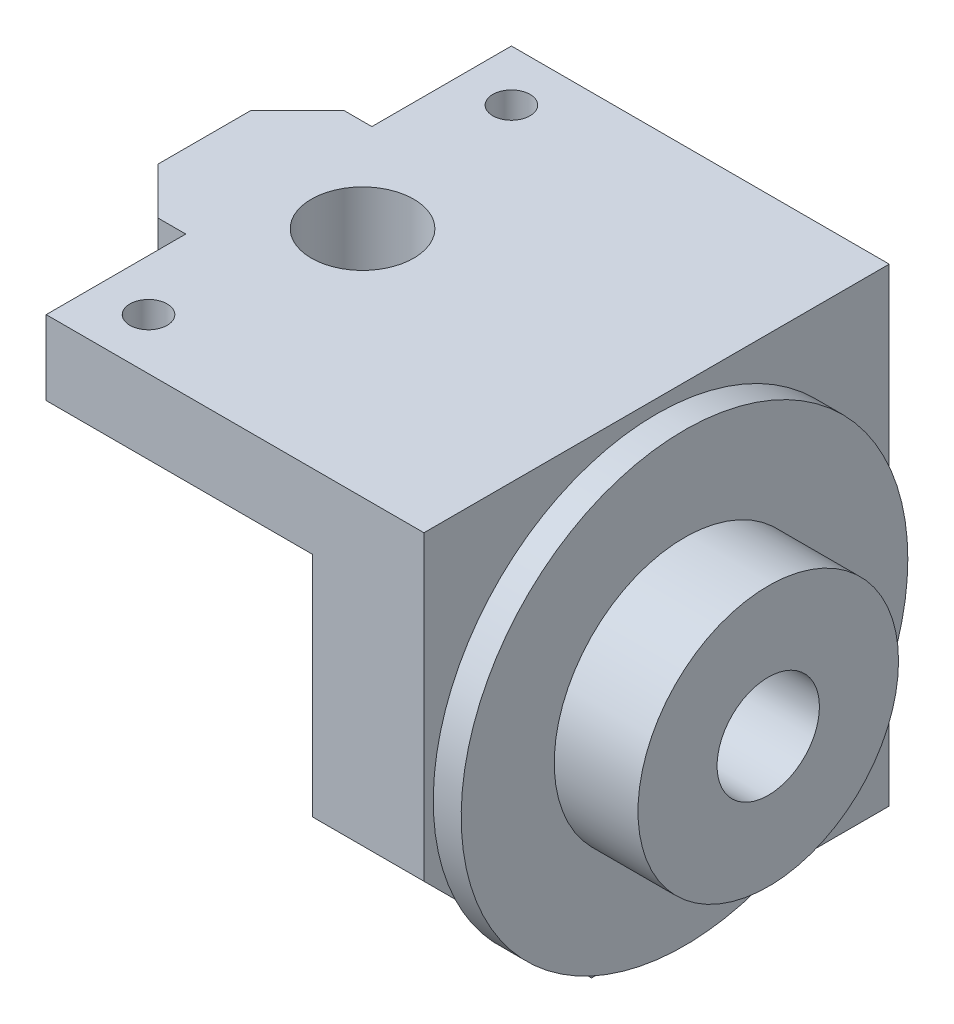
SolidWorks part; units mm, degrees
material "3.0205 (EN-AW 1200)"
ref_plane "Plan de face" through (0, 0, 0) normal (0, 0, 1) x (1, 0, 0)
ref_plane "Plan de dessus" through (0, 0, 0) normal (0, 1, 0) x (1, 0, 0)
ref_plane "Plan de droite" through (0, 0, 0) normal (1, 0, 0) x (0, 0, -1)
sketch "Esquisse1" plane through (0, 0, 0) normal (0, 1, 0) x (1, 0, 0)
  line L1 (-46.9861, 29.5221) -> (-6.3861, 29.5221)
  line L2 (-46.9861, 29.5221) -> (-46.9861, -20.4779)
  line L3 (-46.9861, -20.4779) -> (-6.3861, -20.4779)
  line L4 (-6.3861, 29.5221) -> (-6.3861, -20.4779)
  dimension "D1" = 50
  dimension "D2" = 40.6
extrude "Boss.-Extru.1" add sketch "Esquisse1" along normal blind 8
sketch "Esquisse2" plane through (0, 0, 0) normal (0, -1, 0) x (-1, 0, 0)
  line L0 (6.3861, 29.5221) -> (46.9861, 29.5221) construction
  line L1 (6.3861, -20.4779) -> (18.3861, -20.4779)
  line L2 (6.3861, -20.4779) -> (6.3861, 29.5221)
  line L3 (6.3861, 29.5221) -> (18.3861, 29.5221)
  line L4 (18.3861, -20.4779) -> (18.3861, 29.5221)
  dimension "D1" = 12
extrude "Boss.-Extru.2" add sketch "Esquisse2" along normal blind 42.44
chamfer "Chanfrein1" distance 18 distance2 18 1 edges at (-12.3861, -42.44, 20.4779)
sketch "Esquisse3" plane through (-6.3861, 0, 0) normal (1, 0, 0) x (0, 0, -1)
  line L0 (29.5221, 8) -> (29.5221, -42.44) construction
  line L1 (29.5221, -42.44) -> (-2.4779, -42.44) construction
  circle A0 centre (4.5221, -17.44) radius 24
  dimension "D1" = 48
  dimension "D2" = 25
  dimension "D3" = 25
extrude "Boss.-Extru.3" add sketch "Esquisse3" along normal blind 3
sketch "Esquisse4" plane through (-3.3861, 0, 0) normal (1, 0, 0) x (0, 0, -1)
  circle A0 centre (4.5221, -17.44) radius 14
  circle A1 centre (4.5221, -17.44) radius 24 construction
  dimension "D1" = 28
  dimension "D2" = 0
extrude "Boss.-Extru.4" add sketch "Esquisse4" along normal blind 9
sketch "Esquisse5" plane through (-46.9861, 0, 0) normal (-1, 0, 0) x (0, 0, 1)
  line L0 (-29.5221, 8) -> (20.4779, 8) construction
  line L1 (-14.5221, 8) -> (5.4779, 8)
  line L2 (-14.5221, 8) -> (-14.5221, 0)
  line L3 (-14.5221, 0) -> (5.4779, 0)
  line L4 (5.4779, 8) -> (5.4779, 0)
  line L5 (-29.5221, 0) -> (20.4779, 0) construction
  dimension "D1" = 15
  dimension "D2" = 15
  dimension "D3" = 20
extrude "Boss.-Extru.5" add sketch "Esquisse5" along normal blind 8
chamfer "Chanfrein2" distance 5 angle 45 1 edges at (-54.9861, 4, 5.4779)
chamfer "Chanfrein3" distance 5 angle 45 1 edges at (-54.9861, 4, -14.5221)
sketch "Esquisse6" plane through (0, 8, 0) normal (0, 1, 0) x (1, 0, 0)
  line L1 (-6.3861, 29.5221) -> (-46.9861, 29.5221) construction
  line L2 (-54.9861, -0.4779) -> (-54.9861, 9.5221) construction
  circle A0 centre (-37.9861, 4.5221) radius 5.5
  dimension "D1" = 11
  dimension "D2" = 25
  dimension "D3" = 17
extrude "Enlèv. mat.-Extru.1" cut sketch "Esquisse6" against normal through all
sketch "Esquisse7" plane through (5.6139, 0, 0) normal (1, 0, 0) x (0, 0, -1)
  circle A0 centre (4.5221, -17.44) radius 5.5
  circle A3 centre (4.5221, -17.44) radius 14 construction
  dimension "D1" = 11
  dimension "D2" = 0
extrude "Enlèv. mat.-Extru.2" cut sketch "Esquisse7" against normal through all
sketch "Esquisse8" plane through (0, 8, 0) normal (0, 1, 0) x (1, 0, 0)
  line L2 (-46.9861, -20.4779) -> (-6.3861, -20.4779) construction
  line L3 (-6.3861, 29.5221) -> (-46.9861, 29.5221) construction
  line L4 (-46.9861, -5.4779) -> (-46.9861, -20.4779) construction
  line L5 (-46.9861, 29.5221) -> (-46.9861, 14.5221) construction
  circle A0 centre (-41.4861, -14.9779) radius 2
  circle A1 centre (-41.4861, 24.0221) radius 2
  dimension "D1" = 4
  dimension "D2" = 4
  dimension "D3" = 39
  dimension "D4" = 5.5
  dimension "D5" = 5.5
  dimension "D6" = 5.5
  dimension "D7" = 5.5
ref_plane "Plan6" through (-3.3861, -17.44, -4.5221) normal (0, -1, 0) x (0, 0, 1)
ref_plane "Plan7" through (-54.9861, -17.44, -4.5221) normal (0, -1, 0) x (0, 0, -1)
extrude "Enlèv. mat.-Extru.3" cut sketch "Esquisse8" against normal through all
